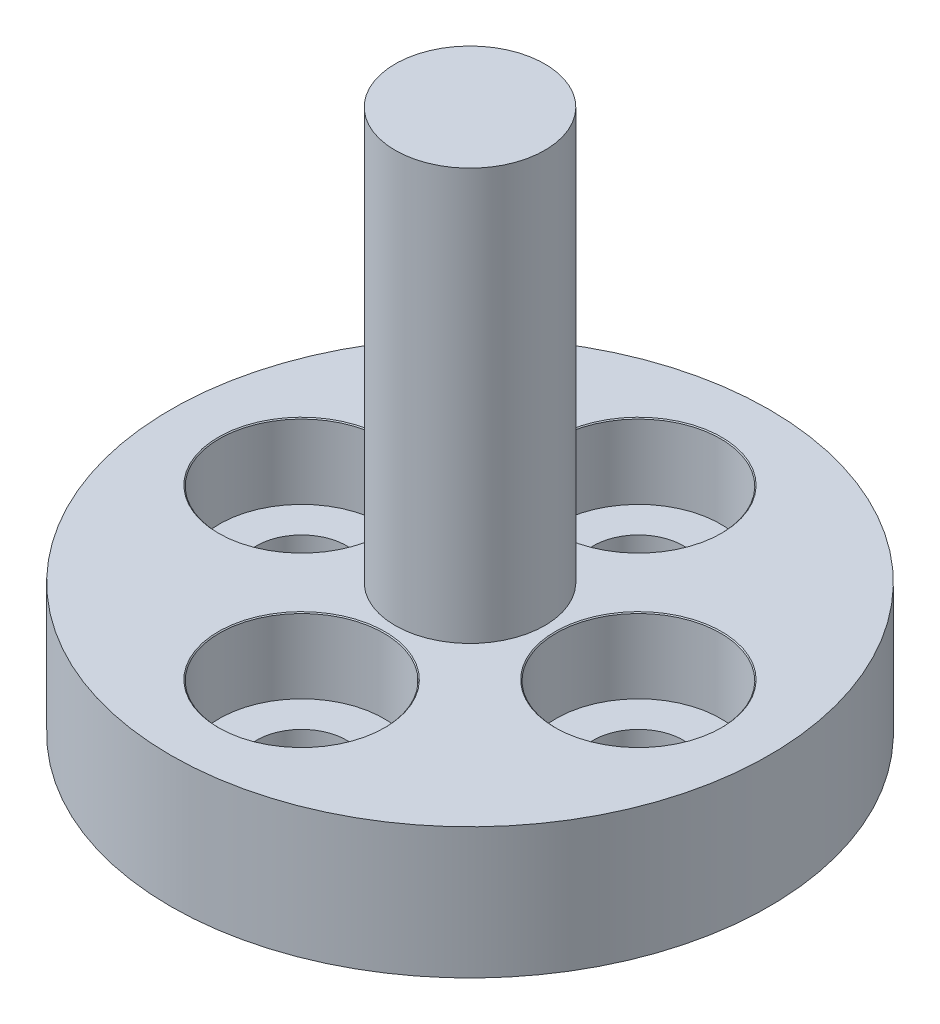
SolidWorks part; units mm, degrees
ref_plane "Front Plane" through (0, 0, 0) normal (0, 0, 1) x (1, 0, 0)
ref_plane "Top Plane" through (0, 0, 0) normal (0, 1, 0) x (1, 0, 0)
ref_plane "Right Plane" through (0, 0, 0) normal (1, 0, 0) x (0, 0, -1)
sketch "Sketch1" plane through (0, 0, 0) normal (0, 0, 1) x (1, 0, 0)
  line L0 (0, 0) -> (8, 0)
  line L1 (8, 0) -> (8, 3.5)
  line L2 (8, 3.5) -> (2, 3.5)
  line L3 (2, 3.5) -> (2, 14.5)
  line L4 (2, 14.5) -> (0, 14.5)
  line L5 (0, 14.5) -> (0, 0)
  dimension "D1" = 8
  dimension "D2" = 14.5
  dimension "D3" = 11
  dimension "D4" = 2
revolve "Revolve1" add sketch "Sketch1" angle 360 about L5
sketch "Sketch3" plane through (0, 3.5, 0) normal (0, 1, 0) x (1, 0, 0)
  circle A0 centre (0, 0) radius 4.5
  dimension "D1" = 9
hole_wizard "CBORE for M2 SHCS1" positions "Sketch4" profile "Sketch5" counterbore size "M2" standard "ANSI Metric" end condition through all
sketch "Sketch4" plane through (0, 3.5, 0) normal (0, 1, 0) x (1, 0, 0)
  circle A0 centre (0, 0) radius 4.5 construction
  point P0 (-4.5, 0)
  point P4 (0, 4.5)
  point P6 (4.5, 0)
  point P8 (0, -4.5)
sketch "Sketch5" plane through (-4.5, 3.5, 0) normal (1, 0, 0) x (0, 0, 1)
  line L0 (0, 0) -> (0, 3.5)
  line L1 (0, 3.5) -> (1.2, 3.5)
  line L3 (1.2, 3.5) -> (1.2, 2)
  line L4 (2.2, 2) -> (1.2, 2)
  line L5 (2.2, 2) -> (2.2, 0.025)
  line L6 (2.2, 0.025) -> (2.225, 0)
  line L7 (2.225, 0) -> (0, 0)
  line L8 (-2.2, 0.025) -> (-2.225, 0) construction
  line L11 (0, -6.35) -> (0, 107.95) construction
  dimension "Thru Hole Dia." = 2.4
  dimension "Thru Hole Depth" = 3.5
  dimension "C'Bore Dia." = 4.4
  dimension "C'Bore Depth" = 2
  dimension "Near C'Sink Dia." = 4.45
  dimension "Near C'Sink Angle" = 90
